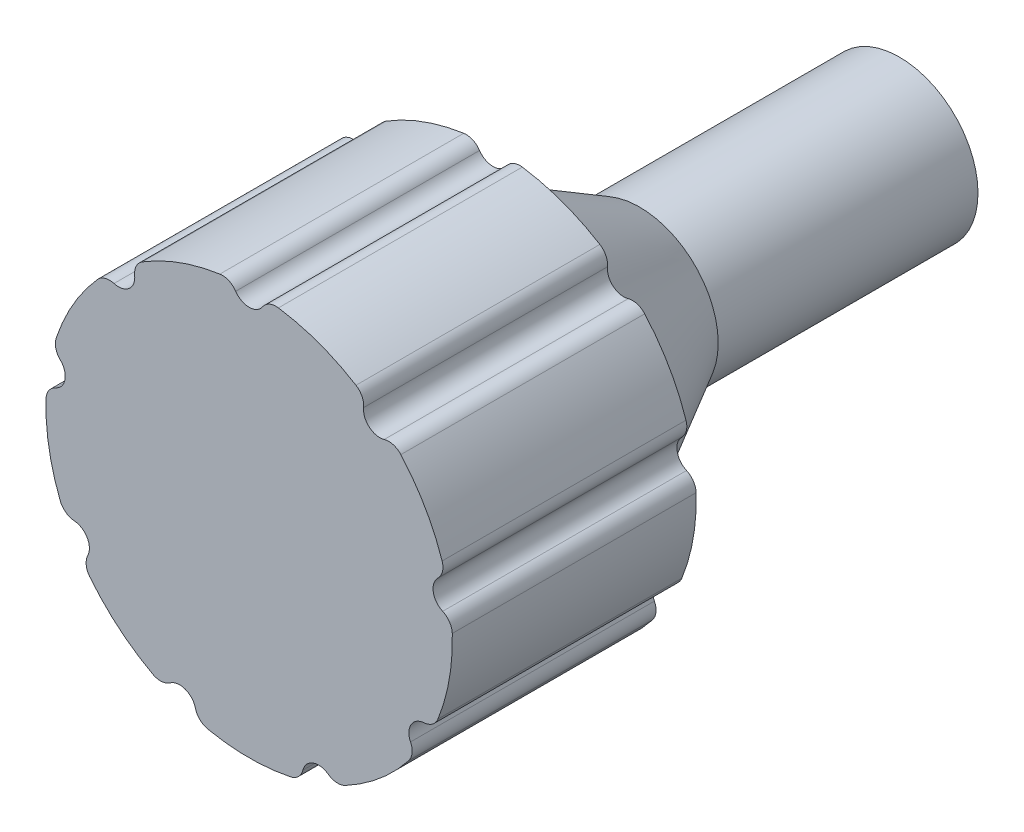
SolidWorks part; units mm, degrees
ref_plane "Спереди" through (0, 0, 0) normal (0, 0, 1) x (1, 0, 0)
ref_plane "Сверху" through (0, 0, 0) normal (0, 1, 0) x (1, 0, 0)
ref_plane "Справа" through (0, 0, 0) normal (1, 0, 0) x (0, 0, -1)
sketch "Эскиз1" plane through (0, 0, 0) normal (0, 0, 1) x (1, 0, 0)
  line L0 (0, 0) -> (0, 2.829) construction
  line L1 (0, 0) -> (2.45, 1.4145) construction
  line L2 (0, 0) -> (2.45, -1.4145) construction
  line L3 (0, 0) -> (0, -2.829) construction
  line L4 (0, 0) -> (-2.45, -1.4145) construction
  line L5 (0, 0) -> (-2.45, 1.4145) construction
  line L6 (0, 2.829) -> (2.45, 1.4145)
  line L7 (2.45, 1.4145) -> (2.45, -1.4145)
  line L8 (2.45, -1.4145) -> (0, -2.829)
  line L9 (0, -2.829) -> (-2.45, -1.4145)
  line L10 (-2.45, -1.4145) -> (-2.45, 1.4145)
  line L11 (-2.45, 1.4145) -> (0, 2.829)
  line L12 (0, 2.829) -> (0, 4.829) construction
  circle A0 centre (0, 0) radius 2.829 construction
  circle A1 centre (0, 0) radius 4.829
  point P11 (0, 0)
  dimension "D2" = 4.9
  dimension "D3" = 2
  dimension "D1" = 6
extrude "Бобышка-Вытянуть1" add sketch "Эскиз1" along normal blind 10
sketch "Эскиз2" plane through (0, 0, 10) normal (0, 0, 1) x (1, 0, 0)
  circle A1 centre (0, 0) radius 4.829
  circle A2 centre (0, 0) radius 4.829
  dimension "D1" = 0
extrude "Бобышка-Вытянуть2" add sketch "Эскиз2" along normal blind 15
sketch "Эскиз3" plane through (0, 0, 25) normal (0, 0, 1) x (1, 0, 0)
  circle A0 centre (0, 0) radius 12.5
  dimension "D1" = 25
extrude "Бобышка-Вытянуть3" add sketch "Эскиз3" along normal blind 15
chamfer "Фаска1" distance 5 angle 61 1 edges at (4.829, 0, 25)
sketch "Эскиз4" plane through (0, 0, 40) normal (0, 0, 1) x (1, 0, 0)
  circle A0 centre (0, 12.5) radius 1
  circle A1 centre (0, 0) radius 12.5 construction
  circle A2 centre (8.0348, 9.5756) radius 1
  circle A3 centre (12.3101, 2.1706) radius 1
  circle A4 centre (10.8253, -6.25) radius 1
  circle A5 centre (4.2753, -11.7462) radius 1
  circle A6 centre (-4.2753, -11.7462) radius 1
  circle A7 centre (-10.8253, -6.25) radius 1
  circle A8 centre (-12.3101, 2.1706) radius 1
  circle A9 centre (-8.0348, 9.5756) radius 1
  point P22 (0, 0)
  dimension "D1" = 2
  dimension "D2" = 9
extrude "Вырез-Вытянуть1" cut sketch "Эскиз4" against normal through all
fillet "Скругление1" radius 1 18 edges at (-12.4442, 1.1796, 32.5) (-12.0972, 3.1477, 32.5) (-10.2911, -7.0953, 32.5) (-11.2903, -5.3647, 32.5) (-3.3226, -12.0503, 32.5) (-5.2005, -11.3668, 32.5) (5.2005, -11.3668, 32.5) (3.3226, -12.0503, 32.5) (11.2903, -5.3647, 32.5) (10.2911, -7.0953, 32.5) (12.0972, 3.1477, 32.5) (12.4442, 1.1796, 32.5) (7.2437, 10.1872, 32.5) (8.7746, 8.9026, 32.5) (-0.9992, 12.46, 32.5) (0.9992, 12.46, 32.5) (-8.7746, 8.9026, 32.5) (-7.2437, 10.1872, 32.5)
